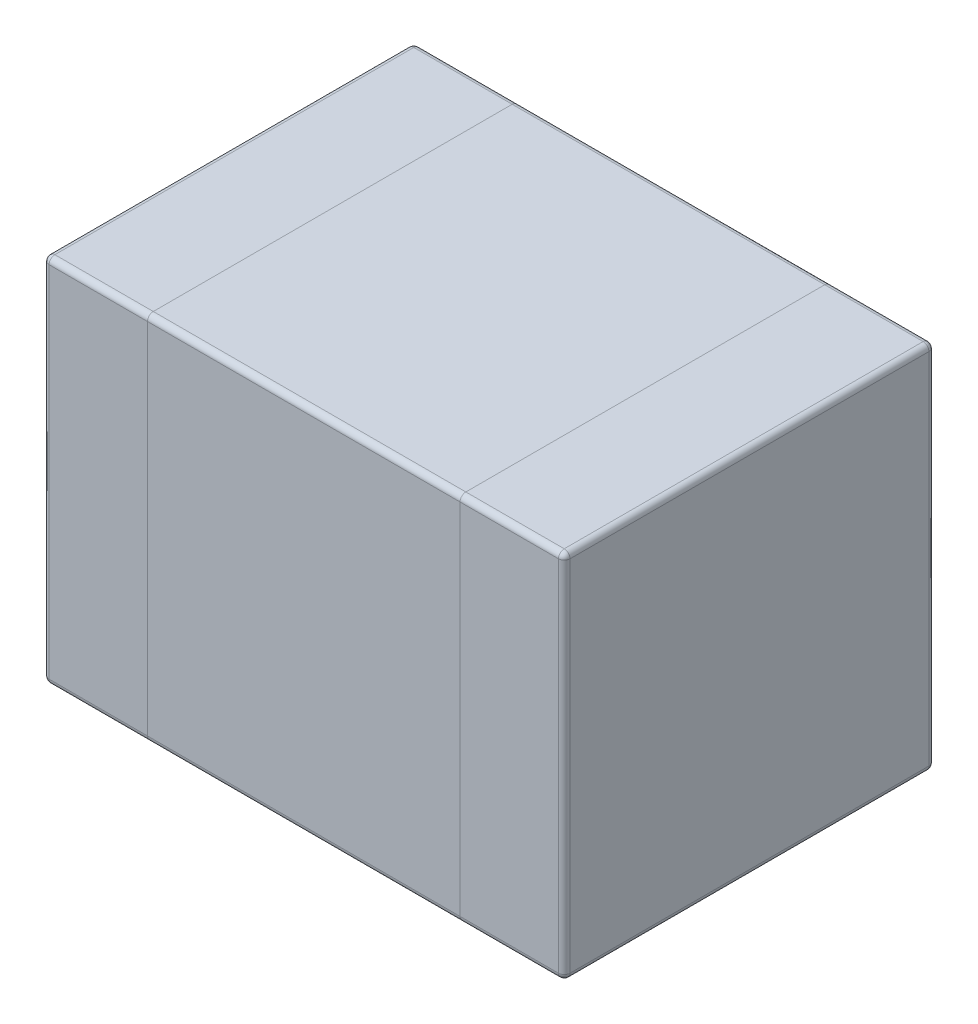
SolidWorks part; units mm, degrees
ref_plane "Front Plane" through (0, 0, 0) normal (0, 0, 1) x (1, 0, 0)
ref_plane "Top Plane" through (0, 0, 0) normal (0, 1, 0) x (1, 0, 0)
ref_plane "Right Plane" through (0, 0, 0) normal (1, 0, 0) x (0, 0, -1)
sketch "Sketch1" plane through (0, 0, 0) normal (0, 1, 0) x (1, 0, 0)
  line L1 (-2.25, -1.6) -> (2.25, -1.6)
  line L2 (-2.25, -1.6) -> (-2.25, 1.6)
  line L3 (-2.25, 1.6) -> (2.25, 1.6)
  line L4 (2.25, -1.6) -> (2.25, 1.6)
  line L5 (-2.25, -1.6) -> (2.25, 1.6) construction
  line L6 (-2.25, 1.6) -> (2.25, -1.6) construction
  point P0 (0, 0)
  dimension "D1" = 4.5
  dimension "D2" = 3.2
extrude "Extrude1" add sketch "Sketch1" along normal blind 3.2
fillet "Fillet1" radius 0.05 12 edges at (2.25, 1.6, -1.6) (-2.25, 1.6, -1.6) (-2.25, 1.6, 1.6) (2.25, 1.6, 1.6) (0, 3.2, 1.6) (-2.25, 3.2, 0) (0, 3.2, -1.6) (2.25, 3.2, 0) (0, 0, -1.6) (-2.25, 0, 0) (0, 0, 1.6) (2.25, 0, 0)
sketch "Sketch2" plane through (0, 0, 0) normal (0, 1, 0) x (1, 0, 0)
  line L0 (-2.2, 1.6) -> (2.2, 1.6) construction
  line L1 (-1.35, -1.6) -> (1.35, -1.6)
  line L2 (-1.35, -1.6) -> (-1.35, 1.6)
  line L3 (-1.35, 1.6) -> (1.35, 1.6)
  line L4 (1.35, -1.6) -> (1.35, 1.6)
  line L5 (2.2, -1.6) -> (-2.2, -1.6) construction
  line L6 (0, 1.55) -> (0, -0.6635) construction
  line L7 (2.2, 1.55) -> (-2.2, 1.55) construction
  line L9 (-2.25, -1.55) -> (-2.25, 1.55) construction
  dimension "D1" = 0.9
split line "Split Line3"
